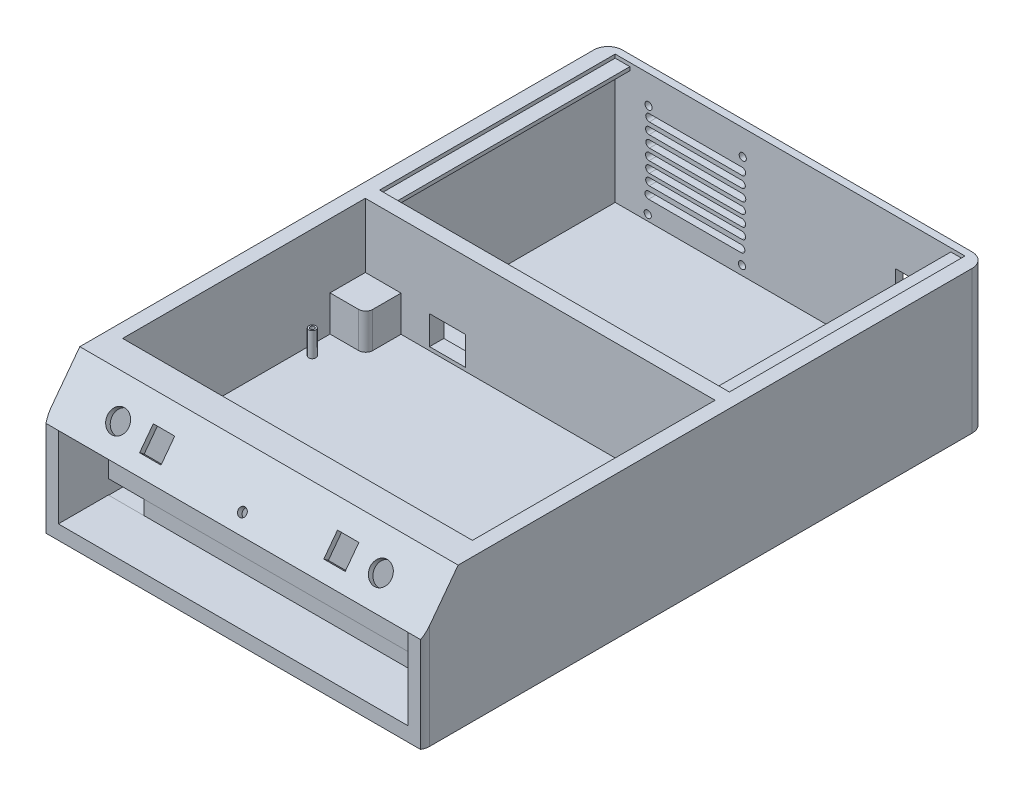
SolidWorks part; units mm, degrees
ref_plane "Front Plane" through (0, 0, 0) normal (0, 0, 1) x (1, 0, 0)
ref_plane "Top Plane" through (0, 0, 0) normal (0, 1, 0) x (1, 0, 0)
ref_plane "Right Plane" through (0, 0, 0) normal (1, 0, 0) x (0, 0, -1)
sketch "Sketch1" plane through (0, 0, 0) normal (0, 1, 0) x (1, 0, 0)
  line L0 (0, -10) -> (0, -390)
  line L1 (10, 0) -> (255, 0)
  line L2 (265, -10) -> (265, -390)
  line L3 (10, -400) -> (255, -400)
  arc A0 (0, -10) -> (10, 0) centre (10, -10) cw
  arc A1 (265, -10) -> (255, 0) centre (255, -10) ccw
  arc A2 (0, -390) -> (10, -400) centre (10, -390) ccw
  arc A3 (265, -390) -> (255, -400) centre (255, -390) cw
extrude "Boss-Extrude2" add sketch "Sketch1" along normal blind 100
ref_plane "Plane1" through (0, 100, 0) normal (0, 1, 0) x (1, 0, 0)
sketch "Sketch4" plane through (0, 100, 0) normal (0, 1, 0) x (1, 0, 0)
  line L0 (0, -10) -> (0, -390) construction
  line L1 (10, -180) -> (255, -180)
  line L2 (10, -180) -> (10, -350)
  line L3 (10, -350) -> (255, -350)
  line L4 (255, -180) -> (255, -350)
  line L5 (10, -400) -> (255, -400) construction
  dimension "D1" = 170
  dimension "D2" = 245
  dimension "D3" = 10
  dimension "D4" = 50
extrude "Cut-Extrude2" cut sketch "Sketch4" against normal blind 70
ref_plane "Plane2" through (132.5, 0, 0) normal (1, 0, 0) x (0, 0, -1)
ref_plane "Plane4" through (0, 0, 360) normal (0, 0, 1) x (1, 0, 0)
sketch "Sketch10" plane through (132.5, 0, 0) normal (1, 0, 0) x (0, 0, -1)
  line L0 (-400, 60) -> (-370, 100)
  line L1 (-400, 100) -> (-400, 0) construction
  line L2 (145.75, 100) -> (-145.75, 100) construction
  line L5 (-360, 55) -> (-360, -55) construction
  line L6 (-400, 60) -> (-400, 100)
  line L7 (-400, 100) -> (-370, 100)
  dimension "D1" = 60
  dimension "D2" = 10
extrude "Cut-Extrude12" cut sketch "Sketch10" against normal through all both and the other way through all
sketch "Sketch14" plane through (132.5, 0, 0) normal (1, 0, 0) x (0, 0, -1)
  line L0 (-390, 10) -> (-360, 10)
  line L1 (-390, 73.3333) -> (-390, 0) construction
  line L2 (-360, 33) -> (-360, -33) construction
  line L7 (-390, 66.6667) -> (-390, 10)
  line L8 (-390, 73.3333) -> (-370, 100) construction
  line L10 (-390, 0) -> (-10, 0) construction
  line L11 (-390, 66.6667) -> (-368, 96)
  line L12 (-368, 96) -> (-360, 96)
  line L13 (-360, 96) -> (-360, 10)
  line L14 (145.75, 100) -> (-145.75, 100) construction
  dimension "D1" = 4
  dimension "D2" = 4
  dimension "D3" = 4
  dimension "D4" = 10
extrude "Cut-Extrude13" cut sketch "Sketch14" against normal mid plane 245
sketch "Sketch15" plane through (132.5, 0, 0) normal (1, 0, 0) x (0, 0, -1)
  line L0 (-360, 33) -> (-360, -33) construction
  line L2 (-360, 9.7841) -> (-360, 20)
  line L3 (-360, 20) -> (-170, 20)
  line L6 (-170, 95) -> (-5, 95)
  line L9 (-5, 95) -> (-5, 10)
  line L10 (0, 100) -> (0, 0) construction
  line L11 (-180, 30) -> (-180, 100) construction
  line L12 (145.75, 100) -> (-145.75, 100) construction
  line L13 (-170, 20) -> (-170, 95)
  line L14 (-5, 10) -> (-360, 9.7841)
  dimension "D1" = 10
  dimension "D2" = 5
  dimension "D5" = 10
  dimension "D6" = 5
extrude "Cut-Extrude14" cut sketch "Sketch15" against normal mid plane 245
sketch "Sketch16" plane through (0, 0, 0) normal (0, 0, -1) x (-1, 0, 0)
  line L0 (-98.8918, 75.7878) -> (-33.8918, 75.7878)
  line L2 (-98.8918, 70.7878) -> (-33.8918, 70.7878)
  line L4 (-98.7106, 67.7878) -> (-33.7106, 67.7878)
  line L5 (-98.7106, 62.9523) -> (-33.7106, 62.9523)
  line L8 (-98.9762, 59.9523) -> (-33.9762, 59.9523)
  line L9 (-98.9762, 54.9523) -> (-33.9762, 54.9523)
  line L10 (-98.7337, 52.1958) -> (-33.7337, 52.1958)
  line L11 (-98.7337, 47.1958) -> (-33.7337, 47.1958)
  line L12 (-98.8646, 44.5988) -> (-33.8646, 44.5988)
  line L13 (-98.8646, 39.5988) -> (-33.8646, 39.5988)
  line L14 (-98.8646, 37.0018) -> (-33.8646, 37.0018)
  line L15 (-98.8646, 32.0018) -> (-33.8646, 32.0018)
  line L16 (-98.3407, 28.6189) -> (-33.3407, 28.6189)
  line L17 (-98.3407, 23.6189) -> (-33.3407, 23.6189)
  line L19 (-235, 20) -> (-206.5, 20)
  line L20 (-235, 20) -> (-235, 68)
  line L21 (-235, 68) -> (-206.5, 68)
  line L22 (-206.5, 20) -> (-206.5, 68)
  line L23 (-10, 20) -> (-255, 20) construction
  line L24 (-255, 100) -> (-255, 0) construction
  line L25 (-10, 10) -> (-255, 10) construction
  circle A36 centre (-99.3515, 82.3468) radius 2.5
  circle A37 centre (-32.7893, 14.2658) radius 2.5
  circle A38 centre (-33.3515, 80.2634) radius 2.5
  circle A39 centre (-98.7893, 16.3492) radius 2.5
  arc A40 (-98.8918, 75.7878) -> (-98.8918, 70.7878) centre (-98.8918, 73.2878) ccw
  arc A41 (-33.8918, 70.7878) -> (-33.8918, 75.7878) centre (-33.8918, 73.2878) ccw
  arc A42 (-98.7106, 67.7878) -> (-98.7106, 62.9523) centre (-98.7106, 65.37) ccw
  arc A43 (-33.7106, 62.9523) -> (-33.7106, 67.7878) centre (-33.7106, 65.37) ccw
  arc A46 (-98.9762, 59.9523) -> (-98.9762, 54.9523) centre (-98.9762, 57.4523) ccw
  arc A47 (-33.9762, 54.9523) -> (-33.9762, 59.9523) centre (-33.9762, 57.4523) ccw
  arc A48 (-98.7337, 52.1958) -> (-98.7337, 47.1958) centre (-98.7337, 49.6958) ccw
  arc A49 (-33.7337, 47.1958) -> (-33.7337, 52.1958) centre (-33.7337, 49.6958) ccw
  arc A50 (-98.8646, 44.5988) -> (-98.8646, 39.5988) centre (-98.8646, 42.0988) ccw
  arc A51 (-33.8646, 39.5988) -> (-33.8646, 44.5988) centre (-33.8646, 42.0988) ccw
  arc A52 (-98.8646, 37.0018) -> (-98.8646, 32.0018) centre (-98.8646, 34.5018) ccw
  arc A53 (-33.8646, 32.0018) -> (-33.8646, 37.0018) centre (-33.8646, 34.5018) ccw
  arc A54 (-98.3407, 28.6189) -> (-98.3407, 23.6189) centre (-98.3407, 26.1189) ccw
  arc A55 (-33.3407, 23.6189) -> (-33.3407, 28.6189) centre (-33.3407, 26.1189) ccw
  circle A56 centre (-241, 44.5988) radius 2.25
  circle A57 centre (-201, 44.5988) radius 2.25
  dimension "D1" = 5
  dimension "D2" = 5
  dimension "D3" = 5
  dimension "D4" = 5
  dimension "D9" = 65
  dimension "D21" = 4.5
  dimension "D5" = 66
  dimension "D6" = 66
  dimension "D7" = 66
  dimension "D8" = 66
  dimension "D10" = 3
  dimension "D11" = 3
  dimension "D12" = 65
  dimension "D13" = 65
  dimension "D14" = 65
  dimension "D15" = 65
  dimension "D16" = 65
  dimension "D17" = 28.5
  dimension "D18" = 48
  dimension "D19" = 20
  dimension "D20" = 10
  dimension "D22" = 40
extrude "Cut-Extrude15" cut sketch "Sketch16" against normal blind 30
sketch "Sketch17" plane through (0, 213.6, 284.8) normal (0, 0.6, 0.8) x (1, 0, 0)
  line L0 (132.5, -55) -> (132.5, 55) construction
  line L1 (60.5, -157) -> (75.5, -157)
  line L2 (60.5, -157) -> (60.5, -173)
  line L3 (60.5, -173) -> (75.5, -173)
  line L4 (75.5, -157) -> (75.5, -173)
  line L5 (189.5, -157) -> (204.5, -157)
  line L6 (189.5, -157) -> (189.5, -173)
  line L7 (189.5, -173) -> (204.5, -173)
  line L8 (204.5, -157) -> (204.5, -173)
  line L9 (0, -142) -> (265, -142) construction
  circle A0 centre (132.5, -173) radius 2.9529
  circle A1 centre (40.5, -164.7277) radius 7.5
  circle A2 centre (224.5, -164.7277) radius 7.5
  dimension "D9" = 15
  dimension "D10" = 15
  dimension "D1" = 16
  dimension "D2" = 15
  dimension "D3" = 16
  dimension "D4" = 57
  dimension "D5" = 57
  dimension "D6" = 15
  dimension "D7" = 15
  dimension "D8" = 15
  dimension "D11" = 20
  dimension "D12" = 20
extrude "Cut-Extrude16" cut sketch "Sketch17" against normal blind 10
sketch "Sketch18" plane through (0, 30, 0) normal (0, 1, 0) x (1, 0, 0)
  line L0 (10, -180) -> (10, -204.7299)
  line L1 (10, -180) -> (10, -350) construction
  line L2 (10, -204.7299) -> (30, -204.7299)
  line L3 (10, -180) -> (34.9927, -180)
  line L4 (34.9927, -180) -> (34.9927, -200)
  line L5 (255, -350) -> (255, -324.1491)
  line L6 (255, -350) -> (255, -180) construction
  line L7 (255, -324.1491) -> (235, -324.1491)
  line L8 (255, -350) -> (230.0729, -350)
  line L9 (10, -350) -> (255, -350) construction
  line L10 (230.0729, -350) -> (230.0729, -330)
  arc A0 (30, -204.7299) -> (34.9927, -200) centre (30, -199.7299) ccw
  arc A1 (235, -324.1491) -> (230.0729, -330) centre (235, -329.1491) ccw
  dimension "D1" = 5
  dimension "D2" = 20
  dimension "D3" = 20
  dimension "D4" = 5
  dimension "D5" = 20
  dimension "D6" = 20
extrude "Boss-Extrude3" add sketch "Sketch18" along normal blind 25
sketch "Sketch19" plane through (0, 0, 180) normal (0, 0, 1) x (1, 0, 0)
  line L0 (10, 55) -> (30, 55) construction
  line L3 (54.9927, 52.5) -> (79.9927, 52.5)
  line L5 (54.9927, 32.5) -> (79.9927, 32.5)
  line L6 (54.9927, 52.5) -> (54.9927, 32.5)
  line L7 (79.9927, 32.5) -> (79.9927, 52.5)
  line L8 (10, 30) -> (230.0729, 30) construction
  line L9 (34.9927, 55) -> (34.9927, 30) construction
  dimension "D1" = 2.5
  dimension "D2" = 2.5
  dimension "D3" = 25
  dimension "D4" = 20
extrude "Cut-Extrude17" cut sketch "Sketch19" against normal blind 15
sketch "Sketch21" plane through (0, 20, 0) normal (0, -1, 0) x (1, 0, 0)
  line L9 (10, 170) -> (255, 170) construction
  line L10 (34.9927, 170) -> (230.0729, 170)
  line L11 (34.9927, 170) -> (34.9927, 360)
  line L12 (34.9927, 360) -> (230.0729, 360)
  line L13 (230.0729, 170) -> (230.0729, 360)
  line L14 (33, 360) -> (-33, 360) construction
extrude "Boss-Extrude9" add sketch "Sketch21" along normal blind 10 separate body
sketch "Sketch23" plane through (0, 0, 400) normal (0, 0, 1) x (1, 0, 0)
  line L1 (0, 0) -> (265, 0)
  line L2 (0, 0) -> (0, 73.3333)
  line L3 (0, 73.3333) -> (265, 73.3333)
  line L4 (265, 0) -> (265, 73.3333)
  ellipse E0 centre (255, 73.3333) end of major axis (255, 60) minor radius 10 (255, 60) -> (265, 73.3333) ccw construction
extrude "Cut-Extrude18" cut sketch "Sketch23" against normal blind 5
sketch "Sketch24" plane through (0, 0, 395) normal (0, 0, 1) x (1, 0, 0)
  line L1 (10, 10) -> (255, 10)
  line L2 (10, 10) -> (10, 66.6667)
  line L3 (10, 66.6667) -> (255, 66.6667)
  line L4 (255, 10) -> (255, 66.6667)
extrude "Cut-Extrude19" cut sketch "Sketch24" against normal blind 5
sketch "Sketch25" plane through (0, 100, 0) normal (0, 1, 0) x (1, 0, 0)
  line L1 (10, -5) -> (255, -5)
  line L2 (10, -5) -> (10, -170)
  line L3 (10, -170) -> (255, -170)
  line L4 (255, -5) -> (255, -170)
extrude "Cut-Extrude21" cut sketch "Sketch25" against normal blind 2.5
sketch "Sketch26" plane through (0, 97.5, 0) normal (0, 1, 0) x (1, 0, 0)
  line L0 (255, -5) -> (10, -5) construction
  line L1 (20.2813, -5) -> (245.1118, -5)
  line L2 (20.2813, -5) -> (20.2813, -170)
  line L3 (20.2813, -170) -> (245.1118, -170)
  line L4 (245.1118, -5) -> (245.1118, -170)
  line L5 (10, -170) -> (255, -170) construction
extrude "Cut-Extrude22" cut sketch "Sketch26" against normal blind 2.5
sketch "Sketch27" plane through (0, 30, 0) normal (0, 1, 0) x (1, 0, 0)
  line L0 (255, -324.1491) -> (235, -324.1491) construction
  line L1 (255, -350) -> (255, -180) construction
  line L2 (10, -180) -> (10, -350) construction
  circle A0 centre (17, -224.1491) radius 1.5
  circle A1 centre (248, -304.1491) radius 2.5
  circle A2 centre (248, -224.1491) radius 2.5
  circle A3 centre (17, -304.1491) radius 2.5
  circle A4 centre (17, -224.1491) radius 2.5
  circle A5 centre (17, -304.1491) radius 1.5
  circle A6 centre (248, -304.1491) radius 1.5
  circle A7 centre (248, -224.1491) radius 1.5
  point P0 (248, -224.4825)
  point P4 (141.0793, -255.644)
  point P5 (246.5772, -302.6662)
  point P10 (275.7185, -318.7522)
  point P13 (248, -211.7455)
  point P14 (0, 0)
  point P17 (18.4063, -304.1491)
  point P22 (17, -263.3189)
  point P23 (17, -224.1491)
  point P24 (14.5, -224.1491)
  dimension "D1" = 3
  dimension "D2" = 5
  dimension "D5" = 5
  dimension "D3" = 20
  dimension "D4" = 7
  dimension "D6" = 80
  dimension "D7" = 7
  dimension "D8" = 7
extrude "Boss-Extrude11" add sketch "Sketch27" along normal blind 17
